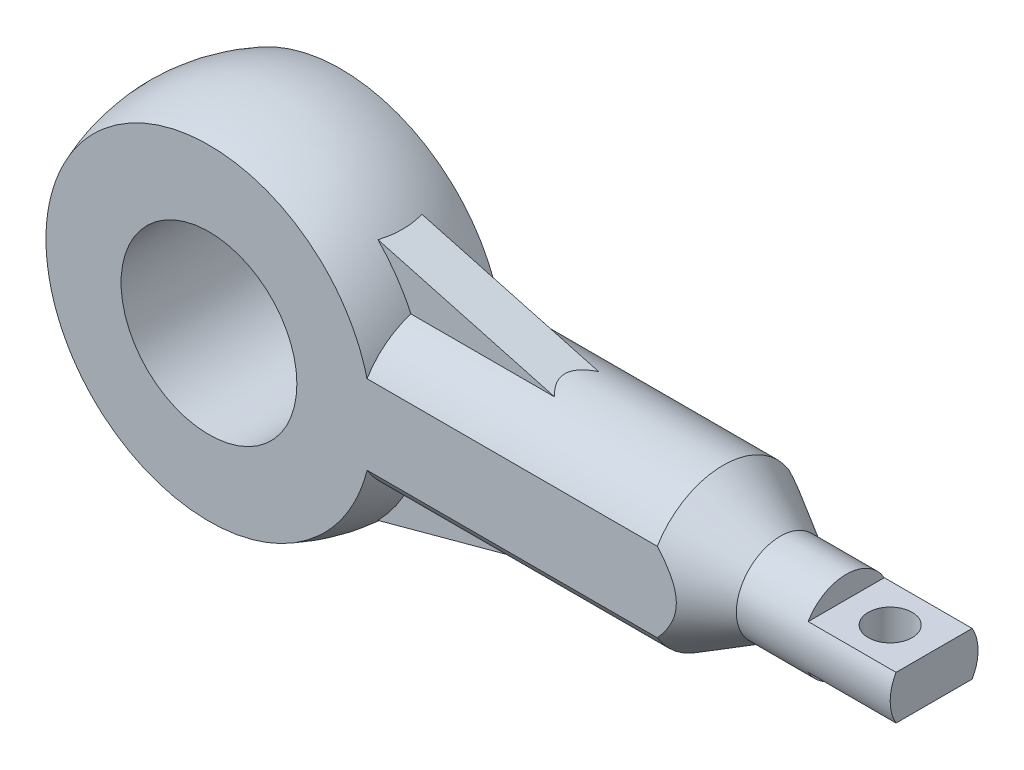
SolidWorks part; units mm, degrees
ref_plane "前视基准面" through (0, 0, 0) normal (0, 0, 1) x (1, 0, 0)
ref_plane "上视基准面" through (0, 0, 0) normal (0, 1, 0) x (1, 0, 0)
ref_plane "右视基准面" through (0, 0, 0) normal (1, 0, 0) x (0, 0, -1)
other "Configuration Table"
sketch "草图2" plane through (0, 0, 0) normal (0, 0, 1) x (1, 0, 0)
  line L0 (0, 0) -> (188.4647, 0) construction
  line L1 (35.9687, 17.5) -> (102.0096, 17.5)
  line L2 (102.0096, 17.5) -> (115, 10)
  line L3 (115, 10) -> (150, 10)
  line L4 (150, 10) -> (150, 0)
  line L5 (-40, 0) -> (40, 0)
  line L6 (150, 0) -> (40, 0)
  arc A0 (35.9687, 17.5) -> (-40, 0) centre (0, 0) ccw
  dimension "D1" = 80
  dimension "D2" = 20
  dimension "D3" = 35
  dimension "D4" = 150
  dimension "D5" = 115
  dimension "D6" = 10
  dimension "D7" = 15
revolve "旋转1" add sketch "草图2" angle 360 about L0
sketch "草图4" plane through (0, 0, 0) normal (0, 0, 1) x (1, 0, 0)
  line L1 (168.7322, 52.3645) -> (-58.8646, 52.3645)
  line L2 (168.7322, 52.3645) -> (168.7322, -47.0684)
  line L3 (168.7322, -47.0684) -> (-58.8646, -47.0684)
  line L4 (-58.8646, 52.3645) -> (-58.8646, -47.0684)
  point P4 (168.7322, -30.7832)
extrude "切除-拉伸1" cut sketch "草图4" against normal blind 10 and the other way blind 40 from offset 25
mirror "镜向1" about plane through (0, 0, 0) normal (0, 0, 1) of "切除-拉伸1"
sketch "草图5" plane through (0, 0, 15) normal (0, 0, 1) x (1, 0, 0)
  circle A0 centre (0, 0) radius 20
  dimension "D1" = 40
extrude "切除-拉伸2" cut sketch "草图5" against normal up to next
sketch "草图6" plane through (0, 0, 0) normal (0, 0, 1) x (1, 0, 0)
  line L0 (150, -10) -> (150, 10) construction
  line L1 (130, 10) -> (150, 10)
  line L2 (130, 10) -> (130, 5)
  line L3 (130, 5) -> (150, 5)
  line L4 (150, 10) -> (150, 5)
  line L5 (115, 10) -> (115, -10) construction
  line L6 (115, -10) -> (150, -10) construction
  line L7 (115, 0) -> (157.4772, 0) construction
  line L8 (130, -5) -> (150, -5)
  line L9 (150, -10) -> (150, -5)
  line L10 (130, -10) -> (130, -5)
  line L11 (130, -10) -> (150, -10)
  dimension "D1" = 15
  dimension "D2" = 15
  dimension "D3" = 20
extrude "切除-拉伸4" cut sketch "草图6" against normal up to next and the other way up to next
sketch "草图8" plane through (0, 5, 0) normal (0, 1, 0) x (1, 0, 0)
  line L0 (130, 0) -> (150, 0) construction
  line L1 (130, -8.6603) -> (130, 8.6603) construction
  line L2 (150, -8.6603) -> (150, 8.6603) construction
  line L3 (140, 8.6603) -> (140, -8.6603) construction
  line L4 (150, 8.6603) -> (130, 8.6603) construction
  line L5 (150, -8.6603) -> (130, -8.6603) construction
  circle A0 centre (140, 0) radius 5
  dimension "D1" = 10
extrude "切除-拉伸5" cut sketch "草图8" against normal up to next
sketch "草图9" plane through (0, 0, 0) normal (0, 0, 1) x (1, 0, 0)
  line L0 (29.0474, 27.5) -> (65.9687, 17.5)
  line L1 (102.0096, 17.5) -> (35.9687, 17.5) construction
  line L2 (35.9687, 17.5) -> (35.9687, 9.0139) construction
  arc A0 (35.9687, 17.5) -> (35.9687, -17.5) centre (0, 0) ccw construction
  dimension "D1" = 10
  dimension "D2" = 30
rib "筋1" sketch "草图9" sketch "草图9" thickness 10 extrusion direction parallel to sketch draft on no parameters "D1"=10
ref_plane "基准面1" through (0, 0, 0) normal (0, -1, 0) x (-1, 0, 0)
mirror "镜向2" about plane through (0, 0, 0) normal (0, -1, 0) of "筋1"
